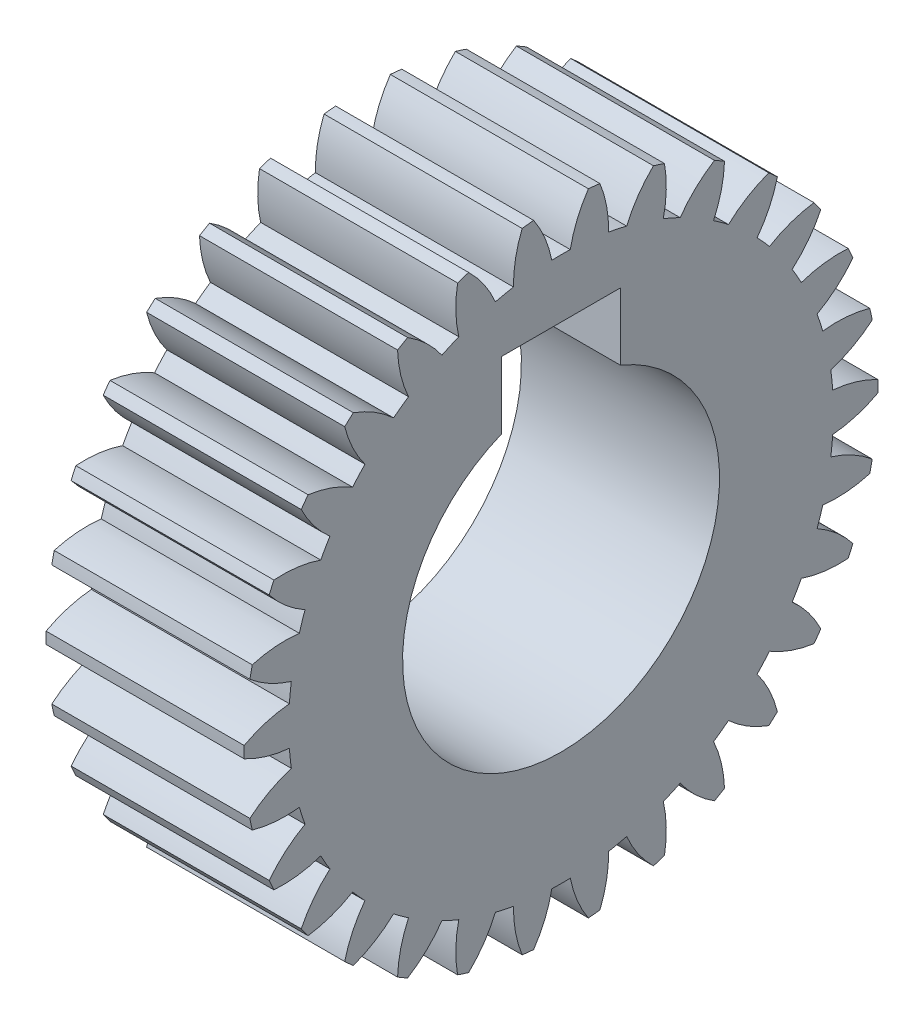
SolidWorks part; units mm, degrees
ref_plane "Plane1" through (0, 0, 0) normal (0, 0, 1) x (1, 0, 0)
ref_plane "Plane2" through (0, 0, 0) normal (0, 1, 0) x (1, 0, 0)
ref_plane "Plane3" through (0, 0, 0) normal (1, 0, 0) x (0, 0, -1)
other "Configuration Table"
sketch "HoldingSke" plane through (0, 0, 0) normal (0, 1, 0) x (1, 0, 0)
  line L0 (0, 0) -> (1.7321, -1)
  line L1 (-15, 0) -> (100, 0) construction
  line L2 (0, 0) -> (-2.1039, 2.3779)
  line L3 (0, 0) -> (-11.863, 4.5341)
  line L4 (0, 0) -> (7.479, 4.318)
  line L5 (0, 0) -> (-46.8476, -17.4728)
  line L6 (0, 0) -> (-4.1448, -2.7965)
  line L7 (-2.1039, 2.3779) -> (8.6586, 51.2059)
  line L8 (-76.2, 54.61) -> (-74.8, 54.61)
  line L9 (-71.009, 38.7566) -> (-53.1078, 45.2721)
  line L10 (-76.2, 71.12) -> (104.1128, 71.12)
  line L11 (0, 0) -> (-5, 0)
  line L12 (-76.2, 101.6) -> (-76.181, 101.6)
  line L13 (24.9733, 27.94) -> (52.9518, 28.4284)
  line L14 (24.9733, 27.94) -> (24.9743, 27.94)
  line L15 (24.9733, 27.94) -> (100.4006, 29.5858)
  line L16 (-63.627, -0.5) -> (-12.827, -0.5)
  circle A0 centre (0, 0) radius 4
  circle A1 centre (0, 0) radius 6.874
  circle A2 centre (0, 0) radius 37.5
  circle A3 centre (0, 0) radius 4
  dimension "MHD" = 13.748
  dimension "Hub_dia" = 75
  dimension "Bore" = 8
  dimension "MBD" = 8
  dimension "Num_teeth" = 30
  dimension "Pitch" = 2
  dimension "Overall_len" = 50
  dimension "Show_teeth" = 30
  dimension "Thickness" = 5
  dimension "OAL" = 50.0001
  dimension "T_dim" = 1.4
  dimension "Ap" = 20
  dimension "H" = 19.05
  dimension "Pitch_radius" = 180.3128
  dimension "Width" = 5
  dimension "Backlash" = 0.019
  dimension "Addendum_fac" = 1
  dimension "Dedendum_fac" = 1.25
  dimension "Clearance_fac" = 0.25
  dimension "Dedendum_add" = 0.001
  dimension "Module" = 0.5
sketch "BasProSke" plane through (0, 0, 0) normal (0, 1, 0) x (1, 0, 0)
  line L0 (-10, 0) -> (60, 0) construction
  line L1 (0, 0) -> (0, 8)
  line L2 (0, 0) -> (5, 0)
  line L3 (5, 0) -> (5, 8)
  line L4 (5, 8) -> (0, 8)
  dimension "Thickness" = 5
  dimension "Diameter" = 16
revolve "Base-Revolve" add sketch "BasProSke" angle 360 about L0
sketch "TooCutSke" plane through (0, 0, 0) normal (1, 0, 0) x (0, 0, -1)
  line L1 (0, 0) -> (0, 107) construction
  line L2 (0, 0) -> (-0.4258, 7.4879) construction
  line L3 (0, 0) -> (-1.5661, 14.9007) construction
  line L4 (-0.4258, 7.4879) -> (-0.7831, 7.4504) construction
  arc A0 (0.2331, 6.87) -> (-0.2331, 6.87) centre (0, 0) ccw
  arc A1 (0.707, 7.9942) -> (-0.707, 7.9942) centre (0, 0) ccw
  circle A2 centre (0, 0) radius 7.5 construction
  circle A3 centre (0, 0) radius 7.0477 construction
  arc A4 (-0.2331, 6.87) -> (-0.707, 7.9942) centre (-3.1767, 6.2911) ccw
  arc A5 (0.707, 7.9942) -> (0.2331, 6.87) centre (3.1767, 6.2911) ccw
  dimension "Root_dia" = 13.748
  dimension "Overcut_dia" = 16.0508
  dimension "Pitch_dia" = 15
  dimension "Base_dia" = 14.0954
  dimension "Flank_rad" = 3
  dimension "Half_ang" = 6
  dimension "Half_CT" = 0.3593
extrude "ToothCut" cut sketch "TooCutSke" along normal through all
fillet "Breaks" [suppressed] radius 0.01
fillet "RootFillets" [suppressed] radius 0.126
pattern_circular "TeethCuts" count 30 every 12 about axis through (-10, 0, 0) along (1, 0, 0) of "ToothCut", "RootFillets", "Breaks"
sketch "HubNeaOneSke" plane through (0, 0, 0) normal (-1, 0, 0) x (0, 0, 1)
  circle A0 centre (0, 0) radius 6.874
  dimension "Diameter" = 13.748
extrude "HubNearOne" [suppressed] add sketch "HubNeaOneSke" along normal blind 45.0001
sketch "HubNeaBotSke" plane through (0, 0, 0) normal (-1, 0, 0) x (0, 0, 1)
  circle A0 centre (0, 0) radius 6.874
  dimension "Diameter" = 13.748
extrude "HubNearBoth" [suppressed] add sketch "HubNeaBotSke" along normal blind 22.5
ref_plane "FarPln" through (5, 0, 0) normal (1, 0, 0) x (0, 0, -1)
sketch "HubFarSke" plane through (5, 0, 0) normal (1, 0, 0) x (0, 0, -1)
  circle A0 centre (0, 0) radius 6.874
  dimension "Diameter" = 13.748
extrude "HubFar" [suppressed] add sketch "HubFarSke" along normal blind 22.5
sketch "BorSke" plane through (0, 0, 0) normal (1, 0, 0) x (0, 0, -1)
  circle A0 centre (0, 0) radius 4
  dimension "Diameter" = 8
extrude "Bore" cut sketch "BorSke" along normal mid plane 100.0001
sketch "KeySke" plane through (0, 0, 0) normal (1, 0, 0) x (0, 0, -1)
  line L0 (-1.5, 0) -> (-1.5, 5.4)
  line L1 (-1.5, 5.4) -> (1.5, 5.4)
  line L2 (1.5, 5.4) -> (1.5, 0)
  line L3 (0, 0) -> (0, 34) construction
  line L4 (-1.5, 0) -> (1.5, 0)
  dimension "Offset" = 5.4
  dimension "Width" = 3
extrude "Keyway" cut sketch "KeySke" along normal mid plane 100.0001
pattern_circular "Keyway2" [suppressed] count 2 every 90 about axis through (-10, 0, 0) along (1, 0, 0)
equation "' \"Module@HoldingSke\" = 6.35"
equation "' \"Num_teeth@HoldingSke\" = 12"
equation "' \"Ap@HoldingSke\" =  20"
equation "' \"Ap@HoldingSke\" = 20"
equation "' \"Width@HoldingSke\" = 0.5 * 25.4"
equation "' \"Hub_dia@HoldingSke\"= 1 * 25.4"
equation "' \"Hub_dia@HoldingSke\" = 1 * 25.4"
equation "' \"Overall_len@HoldingSke\" = 1.0 * 25.4"
equation "' \"Bore@HoldingSke\" = 0.75 * 25.4"
equation "' \"T_dim@HoldingSke\" = 0.1 * 25.4"
equation "' \"Width@KeySke\" = 0.25 * 25.4"
equation "' \"Show_teeth@HoldingSke\" = 13"
equation "' \"Backlash@HoldingSke\" = 0.009 * 25.4"
equation "' \"Addendum_fac@HoldingSke\" = 1.0"
equation "' \"Dedendum_fac@HoldingSke\" = 1.25"
equation "' \"Dedendum_add@HoldingSke\" = 0.00005 * 25.4"
equation "' \"Clearance_fac@HoldingSke\" = 0.25"
equation "\"Pitch@HoldingSke\" = 1 / \"Module@HoldingSke\""
equation "\"Overcut_dia@TooCutSke\" = (\"Num_teeth@HoldingSke\" + 2 * \"Addendum_fac@HoldingSke\") / \"Pitch@HoldingSke\" + 0.002 * 25.4"
equation "\"Pitch_dia@TooCutSke\" = \"Num_teeth@HoldingSke\" / \"Pitch@HoldingSke\""
equation "\"Base_dia@TooCutSke\" = \"Num_teeth@HoldingSke\" / \"Pitch@HoldingSke\" * cos((\"Ap@HoldingSke\"  * 3.14159265 / 180))"
equation "\"Root_dia@TooCutSke\" = (\"Num_teeth@HoldingSke\" + 2) / \"Pitch@HoldingSke\" - 2 * (\"Addendum_fac@HoldingSke\" + \"Dedendum_fac@HoldingSke\") / \"Pitch@HoldingSke\" - \"Dedendum_add@HoldingSke\" * 2"
equation "\"Half_ang@TooCutSke\" = 180 / \"Num_teeth@HoldingSke\""
equation "\"Half_CT@TooCutSke\" = \"Num_teeth@HoldingSke\" / \"Pitch@HoldingSke\" * sin((3.14159265 / 2 / \"Num_teeth@HoldingSke\")) / 2 - 7 * \"Backlash@HoldingSke\" / 4"
equation "\"Flank_rad@TooCutSke\" = \"Num_teeth@HoldingSke\" / \"Pitch@HoldingSke\" / 5"
equation "\"Radius@RootFillets\" = \"Clearance_fac@HoldingSke\" / \"Pitch@HoldingSke\" + \"Dedendum_add@HoldingSke\""
equation "\"Break_rad@Breaks\" = 0.02 / \"Pitch@HoldingSke\""
equation "\"Thickness@HoldingSke\" = \"Width@HoldingSke\""
equation "\"OAL@HoldingSke\" = \"Thickness@HoldingSke\""
equation "\"MHD@HoldingSke\" = (\"Num_teeth@HoldingSke\" + 2) / \"Pitch@HoldingSke\" - 2 * (\"Addendum_fac@HoldingSke\" + \"Dedendum_fac@HoldingSke\")  / \"Pitch@HoldingSke\" - \"Dedendum_add@HoldingSke\" * 2"
equation "\"MBD@HoldingSke\" = (\"Num_teeth@HoldingSke\" + 2) / \"Pitch@HoldingSke\" - 2 * (\"Addendum_fac@HoldingSke\" + \"Dedendum_fac@HoldingSke\")  / \"Pitch@HoldingSke\" - \"Dedendum_add@HoldingSke\" * 2 - 0.002 * 25.4"
equation "\"MHD@HoldingSke\" = ((sgn( \"MHD@HoldingSke\" - \"Hub_dia@HoldingSke\" )-1)*( \"MHD@HoldingSke\" - \"Hub_dia@HoldingSke\" ))/-2+ \"Hub_dia@HoldingSke\""
equation "\"MBD@HoldingSke\" = ((sgn( \"MBD@HoldingSke\" - \"Bore@HoldingSke\" )-1)*( \"MBD@HoldingSke\" - \"Bore@HoldingSke\" ))/-2+ \"Bore@HoldingSke\""
equation "\"OAL@HoldingSke\" = ((sgn( \"OAL@HoldingSke\" - \"Overall_len@HoldingSke\" )+1)*( \"OAL@HoldingSke\" - \"Overall_len@HoldingSke\" ))/2 + \"Overall_len@HoldingSke\" + 0.000002 * 25.4"
equation "\"Num_teeth@TeethCuts\" = int( \"Show_teeth@HoldingSke\" ) + 1"
equation "\"Num_teeth@TeethCuts\" = ((sgn( \"Num_teeth@TeethCuts\" - \"Num_teeth@HoldingSke\" )-1)*( \"Num_teeth@TeethCuts\" - \"Num_teeth@HoldingSke\" ))/-2+ \"Num_teeth@HoldingSke\""
equation "\"Num_teeth@TeethCuts\" = ((sgn( \"Num_teeth@TeethCuts\" - 2.0)+1)*( \"Num_teeth@TeethCuts\" - 2.0))/2 +2.0"
equation "\"Angle@TeethCuts\" = 360.0 / \"Num_teeth@HoldingSke\""
equation "\"Diameter@BasProSke\" = (\"Num_teeth@HoldingSke\" + 2 * \"Addendum_fac@HoldingSke\") / \"Pitch@HoldingSke\""
equation "\"Thickness@BasProSke\"  = \"Thickness@HoldingSke\""
equation "' \"Fillet_rad@BasProSke\" =  \"Thickness@HoldingSke\" * 0.05"
equation "' \"Fillet_rad@BasProSke\" = \"Thickness@HoldingSke\" * 0.05"
equation "\"MHD@HoldingSke\" = ((sgn( \"MHD@HoldingSke\" - \"Root_dia@TooCutSke\" )-1)*( \"MHD@HoldingSke\" - \"Root_dia@TooCutSke\" ))/-2+ \"Root_dia@TooCutSke\""
equation "\"Diameter@HubNeaOneSke\" = \"MHD@HoldingSke\""
equation "\"Length@HubNearOne\" = \"OAL@HoldingSke\" - \"Thickness@BasProSke\""
equation "\"Diameter@HubNeaBotSke\" = \"MHD@HoldingSke\""
equation "\"Length@HubNearBoth\" = ( \"OAL@HoldingSke\" - \"Thickness@BasProSke\" ) / 2.0"
equation "\"Thickness@FarPln\" = \"Thickness@BasProSke\""
equation "\"Diameter@HubFarSke\" = \"MHD@HoldingSke\""
equation "\"Length@HubFar\" = ( \"OAL@HoldingSke\" - \"Thickness@BasProSke\" ) / 2.0"
equation "\"Diameter@BorSke\" = \"MBD@HoldingSke\""
equation "\"D1@Bore\" = \"OAL@HoldingSke\" * 2.0"
equation "\"D1@Keyway\" = \"OAL@HoldingSke\" * 2.0"
equation "\"Offset@KeySke\" = \"T_dim@HoldingSke\" + \"MBD@HoldingSke\" / 2.0"
